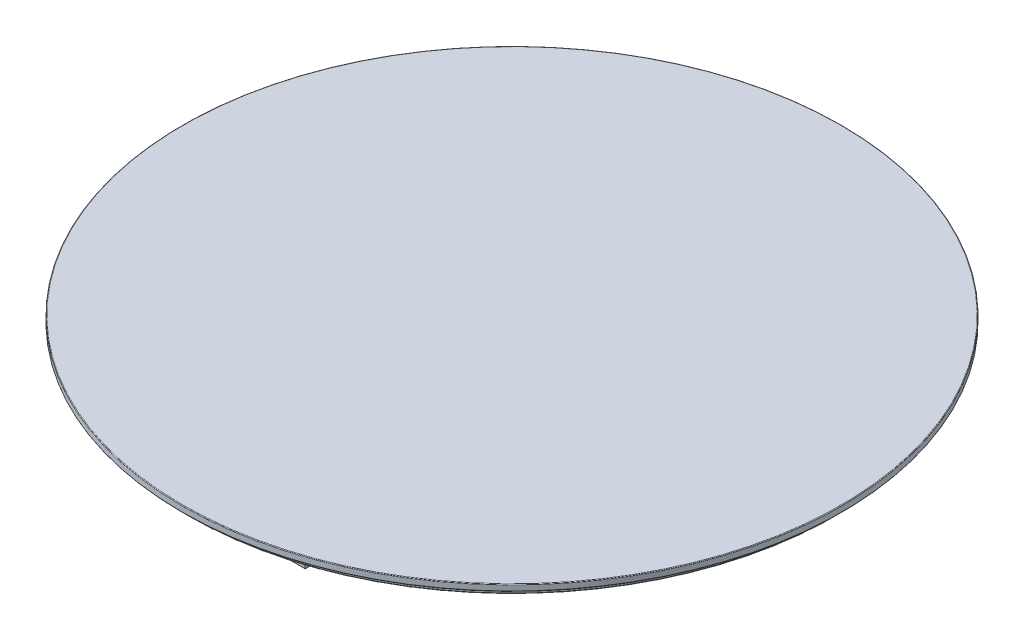
SolidWorks part; units mm, degrees
ref_plane "Front Plane" through (0, 0, 0) normal (0, 0, 1) x (1, 0, 0)
ref_plane "Top Plane" through (0, 0, 0) normal (0, 1, 0) x (1, 0, 0)
ref_plane "Right Plane" through (0, 0, 0) normal (1, 0, 0) x (0, 0, -1)
sketch "Sketch1" plane through (0, 0, 0) normal (0, 1, 0) x (1, 0, 0)
  circle A0 centre (0, 0) radius 255
  dimension "D1" = 510
extrude "Boss-Extrude1" add sketch "Sketch1" along normal blind 10
sketch "Sketch4" plane through (0, 0, 0) normal (0, -1, 0) x (-1, 0, 0)
  circle A0 centre (0, 0) radius 255
  circle A1 centre (0, 0) radius 250
  circle A2 centre (0, 0) radius 255
  circle M1 centre (0, 0) radius 255
  dimension "D1" = 500
  dimension "D2" = 510
extrude "Cut-Extrude1" cut sketch "Sketch4" against normal blind 5 contours A1 M1
fillet "Fillet1" radius 0.5 3 edges at (0, 10, 255) (0, 5, -255) (0, 0, -250)
sketch "Sketch5" plane through (0, 0, 0) normal (0, -1, 0) x (1, 0, 0)
  line L0 (0, -5.5) -> (0, 5.5) construction
  line L1 (-60, 50) -> (60, 50)
  line L2 (-60, 50) -> (-60, 220)
  line L3 (-60, 220) -> (60, 220)
  line L4 (60, 50) -> (60, 220)
  line L5 (-60, 50) -> (60, 220) construction
  line L6 (-60, 220) -> (60, 50) construction
  line L7 (5.5, 0) -> (-5.5, 0) construction
  point P0 (0, 135)
  dimension "D1" = 120
  dimension "D2" = 170
  dimension "D3" = 220
extrude "Boss-Extrude3" add sketch "Sketch5" along normal blind 20
sketch "Sketch7" plane through (0, 0, 0) normal (0, 0, 1) x (1, 0, 0)
  line L0 (0, -25.9939) -> (0, 37.6016) construction
  line L1 (0, -16.5) -> (0, 16.5) construction
pattern_circular "CirPattern2" count 3 over 360 about axis through (0, 0, 0) along (0, 1, 0) of "Boss-Extrude3"
sketch "Sketch6" plane through (0, -20, 0) normal (0, -1, 0) x (1, 0, 0)
  line L14 (-55, 55) -> (55, 55)
  line L15 (-55, 215) -> (-55, 55)
  line L16 (55, 215) -> (-55, 215)
  line L17 (55, 55) -> (55, 215)
  line L18 (-55, 55) -> (55, 55)
  line L19 (-55, 215) -> (-55, 55)
  line L20 (55, 215) -> (-55, 215)
  line L21 (55, 55) -> (55, 215)
  dimension "D1" = 5
extrude "Cut-Extrude3" cut sketch "Sketch6" against normal blind 20
pattern_circular "CirPattern4" count 3 over 360 about axis through (0, 0, 0) along (0, 1, 0) of "Cut-Extrude3"
